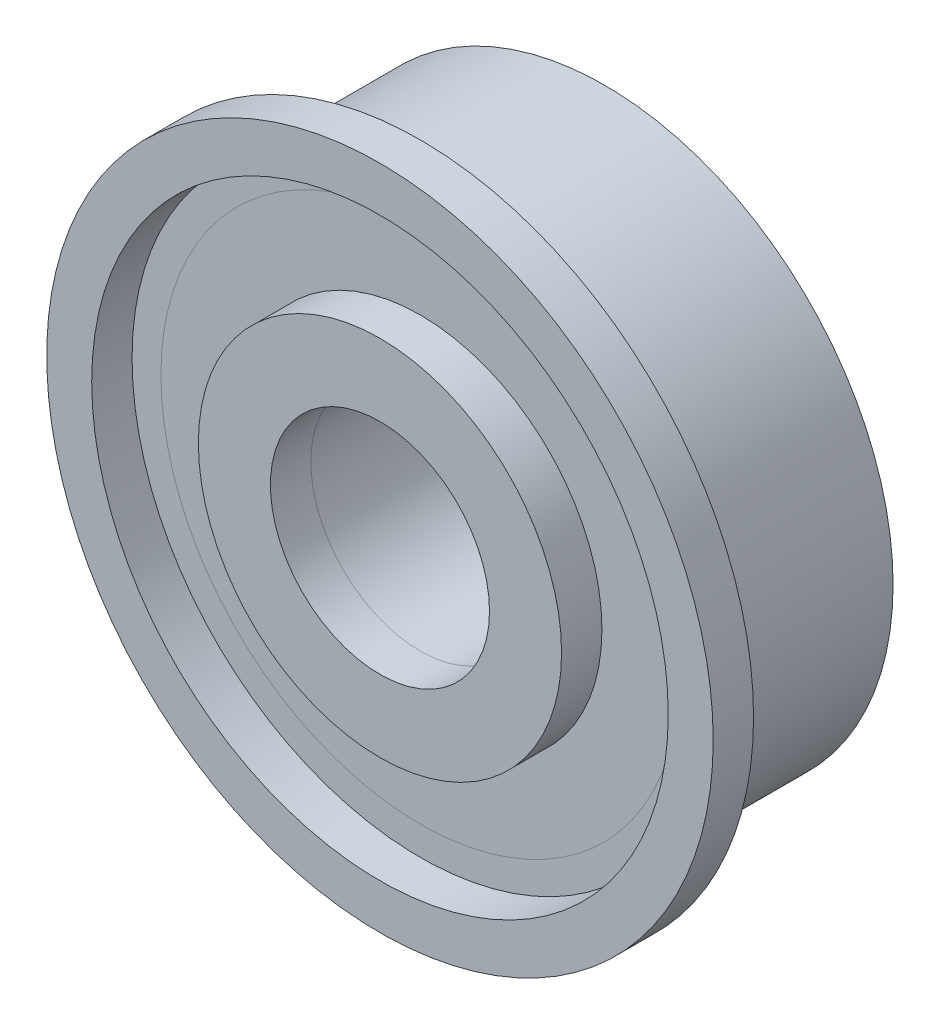
SolidWorks part; units mm, degrees
ref_plane "前视基准面" through (0, 0, 0) normal (0, 0, 1) x (1, 0, 0)
ref_plane "上视基准面" through (0, 0, 0) normal (0, 1, 0) x (1, 0, 0)
ref_plane "右视基准面" through (0, 0, 0) normal (1, 0, 0) x (0, 0, -1)
sketch "草图1" plane through (0, 0, 0) normal (0, 0, 1) x (1, 0, 0)
  circle A0 centre (0, 0) radius 1.9
  circle A1 centre (0, 0) radius 3.15
  dimension "D1" = 3.8
  dimension "D2" = 6.3
extrude "凸台-拉伸1" add sketch "草图1" along normal blind 3.2
sketch "草图2" plane through (0, 0, 3.2) normal (0, 0, 1) x (1, 0, 0)
  circle A0 centre (0, 0) radius 5
  circle A1 centre (0, 0) radius 4.5
  dimension "D1" = 10
  dimension "D2" = 0.5
extrude "凸台-拉伸2" add sketch "草图2" against normal up to surface (3.2 mm away) separate body up to face at (3.15, 0, 0)
sketch "草图3" plane through (0, 0, 3.2) normal (0, 0, 1) x (1, 0, 0)
  circle A0 centre (0, 0) radius 3.15 construction
  circle A1 centre (0, 0) radius 3.15
  circle A2 centre (0, 0) radius 4.5 construction
  circle A3 centre (0, 0) radius 4.5
extrude "凸台-拉伸4" add sketch "草图3" against normal blind 3.2 separate body
sketch "草图4" plane through (0, 0, 3.2) normal (0, 0, 1) x (1, 0, 0)
  circle A0 centre (0, 0) radius 5 construction
  circle A1 centre (0, 0) radius 5
  circle A2 centre (0, 0) radius 5.78
  dimension "D1" = 11.56
extrude "凸台-拉伸6" add sketch "草图4" along normal blind 0.7 separate body
sketch "草图5" plane through (0, 0, 3.2) normal (0, 0, 1) x (1, 0, 0)
  circle A0 centre (0, 0) radius 1.9 construction
  circle A1 centre (0, 0) radius 3.15
  circle A2 centre (0, 0) radius 3.15
  circle A3 centre (0, 0) radius 1.9
  dimension "D1" = 0
extrude "凸台-拉伸7" add sketch "草图5" along normal up to surface (0.7 mm away) separate body up to face at (5.78, 0, 3.9)
